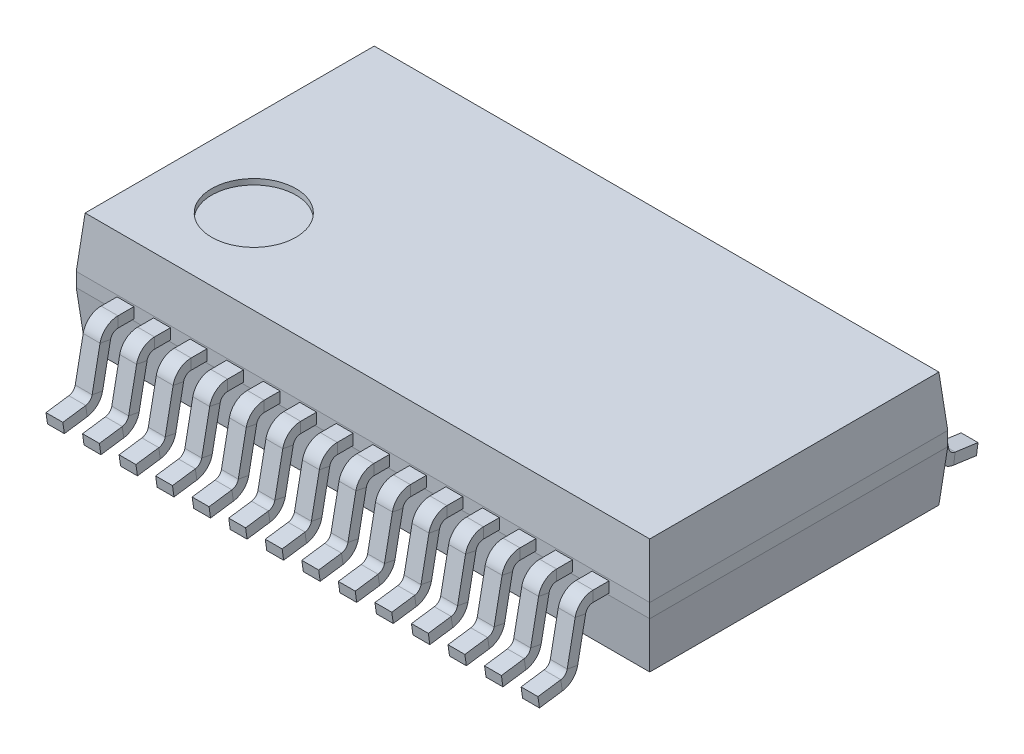
SolidWorks part; units mm, degrees
ref_plane "Front Plane" through (0, 0, 0) normal (0, 0, 1) x (1, 0, 0)
ref_plane "Top Plane" through (0, 0, 0) normal (0, 1, 0) x (1, 0, 0)
ref_plane "Right Plane" through (0, 0, 0) normal (1, 0, 0) x (0, 0, -1)
sketch "Sketch1" plane through (0, 0, 0) normal (0, 1, 0) x (1, 0, 0)
  line L1 (0, 0) -> (10.2, 0)
  line L2 (0, 0) -> (0, 5.3)
  line L3 (0, 5.3) -> (10.2, 5.3)
  line L4 (10.2, 0) -> (10.2, 5.3)
  dimension "D1" = 5.3
  dimension "D2" = 10.2
extrude "Boss-Extrude1" add sketch "Sketch1" along normal blind 0.25
sketch "Sketch2" plane through (0, 0.25, 0) normal (0, 1, 0) x (1, 0, 0)
  line L1 (0, 0) -> (10.2, 0)
  line L2 (0, 0) -> (0, 5.3)
  line L3 (0, 5.3) -> (10.2, 5.3)
  line L4 (10.2, 0) -> (10.2, 5.3)
extrude "Boss-Extrude2" add sketch "Sketch2" along normal blind 0.9 draft 5
sketch "Sketch3" plane through (0, 0, 0) normal (0, -1, 0) x (1, 0, 0)
  line L1 (0, 0) -> (10.2, 0)
  line L2 (0, 0) -> (0, -5.3)
  line L3 (0, -5.3) -> (10.2, -5.3)
  line L4 (10.2, 0) -> (10.2, -5.3)
extrude "Boss-Extrude3" add sketch "Sketch3" along normal blind 0.9 draft 5
sketch "Sketch4" plane through (0, 0, 0) normal (0, 0, 1) x (1, 0, 0)
  line L0 (0, 0.125) -> (0.875, 0.125) construction
  line L1 (0.725, 0.03) -> (1.025, 0.03)
  line L2 (0.725, 0.03) -> (0.725, 0.22)
  line L3 (0.725, 0.22) -> (1.025, 0.22)
  line L4 (1.025, 0.03) -> (1.025, 0.22)
  line L5 (0.725, 0.03) -> (1.025, 0.22) construction
  line L6 (0.725, 0.22) -> (1.025, 0.03) construction
  line L7 (0, 0.25) -> (0, 0) construction
  point P0 (0.875, 0.125)
  dimension "D1" = 0.875
  dimension "D2" = 0.19
  dimension "D3" = 0.3
sketch "Sketch5" plane through (0, 0, 0) normal (1, 0, 0) x (0, 0, -1)
  line L0 (0, 0.125) -> (-0.2829, 0.125)
  line L1 (0, 0.25) -> (0, 0) construction
  line L2 (-0.5086, -0.0609) -> (-0.65, -0.7843)
  line L3 (-0.8437, -0.9679) -> (-1.25, -1.025)
  line L4 (-1.25, -1.025) -> (0, -1.025) construction
  line L5 (0, 0.125) -> (0, -1.025) construction
  arc A0 (-0.2829, 0.125) -> (-0.5086, -0.0609) centre (-0.2829, -0.105) ccw
  arc A1 (-0.65, -0.7843) -> (-0.8437, -0.9679) centre (-0.8757, -0.7401) cw
  point P10 (-0.84, -0.7843)
  dimension "D2" = 0.23
  dimension "D1" = 1.25
  dimension "D3" = 1.15
  dimension "D4" = 0.6
  dimension "D5" = 8
sweep "Sweep1" add profiles "Sketch4" path "Sketch5"
pattern_linear "LPattern1" count 14 spacing 0.65 along (1, 0, 0) of "Sweep1"
ref_plane "Plane1" through (0, 0, -2.65) normal (0, 0, 1) x (1, 0, 0)
mirror "Mirror1" about plane through (0, 0, -2.65) normal (0, 0, 1) of "LPattern1", "Sweep1"
sketch "Sketch6" plane through (0, 1.15, 0) normal (0, 1, 0) x (1, 0, 0)
  line L0 (1.5787, 1.5787) -> (1.5787, 0.0787) construction
  line L1 (0.0787, 0.0787) -> (10.1213, 0.0787) construction
  line L2 (1.5787, 1.5787) -> (0.0787, 1.5787) construction
  line L3 (0.0787, 5.2213) -> (0.0787, 0.0787) construction
  circle A0 centre (1.5787, 1.5787) radius 0.75
  dimension "D2" = 1.5
  dimension "D1" = 1.5
extrude "Cut-Extrude1" cut sketch "Sketch6" against normal blind 0.1
